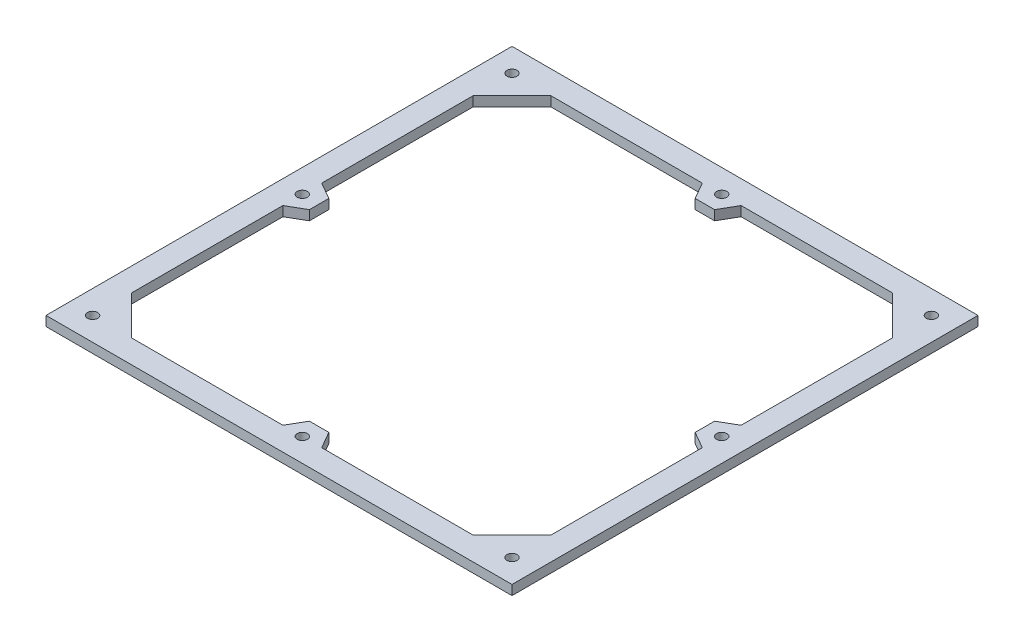
SolidWorks part; units mm, degrees
ref_plane "Front Plane" through (0, 0, 0) normal (0, 0, 1) x (1, 0, 0)
ref_plane "Top Plane" through (0, 0, 0) normal (0, 1, 0) x (1, 0, 0)
ref_plane "Right Plane" through (0, 0, 0) normal (1, 0, 0) x (0, 0, -1)
sketch "Sketch1" plane through (0, 0, 0) normal (0, 1, 0) x (1, 0, 0)
  line L0 (69.85, 7.62) -> (20.32, 7.62)
  line L1 (0, 0) -> (152.4, 0)
  line L2 (0, 0) -> (0, 152.4)
  line L3 (0, 152.4) -> (152.4, 152.4)
  line L4 (152.4, 0) -> (152.4, 152.4)
  line L5 (69.85, 144.78) -> (73.025, 139.2807)
  line L6 (73.025, 139.2807) -> (79.375, 139.2807)
  line L7 (79.375, 139.2807) -> (82.55, 144.78)
  line L8 (7.62, 132.08) -> (20.32, 144.78)
  line L9 (132.08, 144.78) -> (144.78, 132.08)
  line L10 (144.78, 20.32) -> (132.08, 7.62)
  line L11 (7.62, 20.32) -> (20.32, 7.62)
  line L12 (82.55, 144.78) -> (132.08, 144.78)
  line L13 (7.62, 20.32) -> (7.62, 69.85)
  line L14 (20.32, 144.78) -> (69.85, 144.78)
  line L15 (7.62, 82.55) -> (7.62, 132.08)
  line L16 (144.78, 69.85) -> (144.78, 20.32)
  line L17 (144.78, 132.08) -> (144.78, 82.55)
  line L19 (132.08, 7.62) -> (82.55, 7.62)
  line L21 (7.62, 69.85) -> (13.1193, 73.025)
  line L22 (82.55, 7.62) -> (79.375, 13.1193)
  line L23 (79.375, 13.1193) -> (73.025, 13.1193)
  line L24 (73.025, 13.1193) -> (69.85, 7.62)
  line L25 (71.4375, 4.8704) -> (73.3588, 1.5426) [skipped]
  line L26 (73.025, 2.1207) -> (80.7101, 2.1207) [skipped]
  line L27 (80.9625, 4.8704) -> (82.8838, 8.1981) [skipped]
  line L28 (74.1217, 152.1788) -> (72.2004, 148.851) [skipped]
  line L29 (81.5684, 150.2793) -> (73.8832, 150.2793) [skipped]
  line L30 (79.0881, 150.7763) -> (77.1668, 154.104) [skipped]
  line L31 (13.1193, 73.025) -> (13.1193, 79.375)
  line L32 (13.1193, 79.375) -> (7.62, 82.55)
  line L33 (144.78, 82.55) -> (139.2807, 79.375)
  line L34 (139.2807, 79.375) -> (139.2807, 73.025)
  line L35 (139.2807, 73.025) -> (144.78, 69.85)
  line L39 (153.5694, 74.9246) -> (153.7107, 75.0061) [skipped]
  line L40 (150.2793, 69.1237) -> (150.2793, 78.0856) [skipped]
  line L41 (153.6579, 77.4243) -> (153.5166, 77.5059) [skipped]
  line L42 (2.2208, 79.4328) -> (2.0796, 79.3512) [skipped]
  line L43 (2.1207, 79.375) -> (2.1207, 70.4131) [skipped]
  line L44 (2.1207, 73.025) -> (2.262, 72.9434) [skipped]
  circle A0 centre (7.62, 7.62) radius 1.6637
  circle A1 centre (7.62, 144.78) radius 1.6637
  circle A2 centre (144.78, 144.78) radius 1.6637
  circle A3 centre (144.78, 7.62) radius 1.6637
  circle A4 centre (76.2, 7.62) radius 1.6637
  circle A5 centre (76.2, 144.78) radius 1.6637
  circle A6 centre (144.78, 76.2) radius 1.6637
  circle A7 centre (7.62, 76.2) radius 1.6637
  dimension "D12" = 7.62
  dimension "D3" = 3.3274
  dimension "D6" = 3.3274
  dimension "D7" = 3.3274
  dimension "D8" = 3.3274
  dimension "D27" = 3.3274
  dimension "D28" = 3.3274
  dimension "D29" = 3.3274
  dimension "D30" = 3.3274
  dimension "D1" = 152.4
  dimension "D2" = 152.4
  dimension "D4" = 7.62
  dimension "D5" = 7.62
  dimension "D9" = 7.62
  dimension "D10" = 7.62
  dimension "D11" = 7.62
  dimension "D13" = 7.62
  dimension "D14" = 7.62
  dimension "D15" = 12.7
  dimension "D16" = 12.7
  dimension "D17" = 12.7
  dimension "D18" = 12.7
  dimension "D19" = 12.7
  dimension "D20" = 12.7
  dimension "D21" = 12.7
  dimension "D22" = 12.7
  dimension "D23" = 6.35
  dimension "D24" = 6.35
  dimension "D25" = 6.35
  dimension "D26" = 6.35
extrude "Boss-Extrude4" add sketch "Sketch1" along normal blind 3.175
